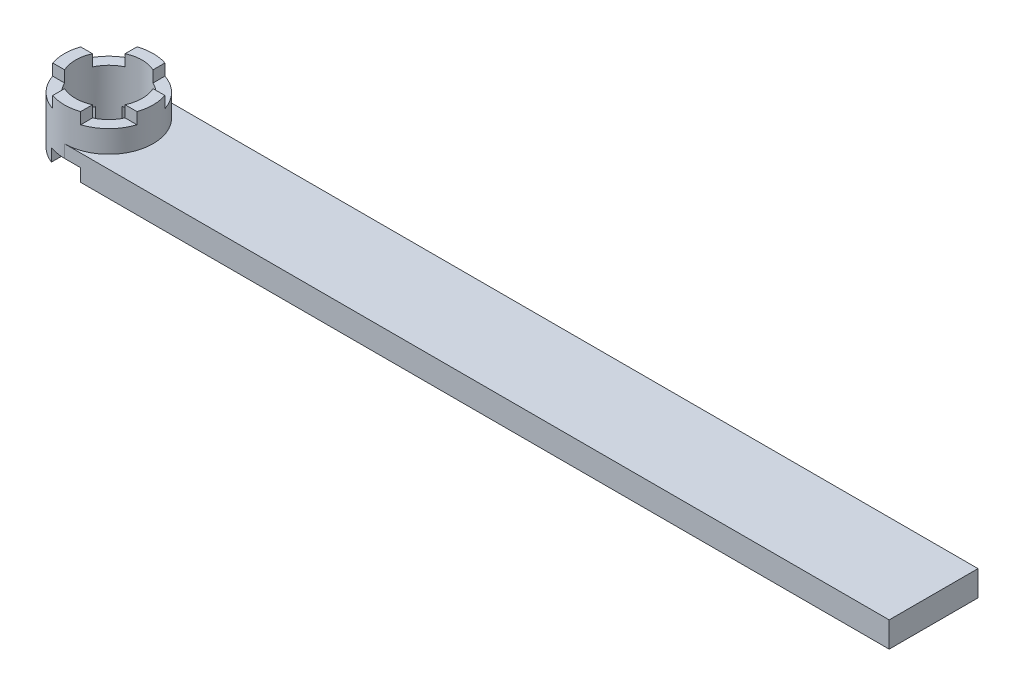
SolidWorks part; units mm, degrees
ref_plane "前视基准面" through (0, 0, 0) normal (0, 0, 1) x (1, 0, 0)
ref_plane "上视基准面" through (0, 0, 0) normal (0, 1, 0) x (1, 0, 0)
ref_plane "右视基准面" through (0, 0, 0) normal (1, 0, 0) x (0, 0, -1)
other "Configuration Table"
sketch "草图1" plane through (0, 0, 0) normal (0, 1, 0) x (1, 0, 0)
  line L1 (0, 7) -> (130, 7)
  line L3 (0, -7) -> (130, -7)
  line L4 (130, 7) -> (130, -7)
  circle A0 centre (0, 0) radius 5.25
  circle A1 centre (0, 0) radius 7
  dimension "D1" = 10.5
  dimension "D2" = 14
  dimension "D3" = 130
extrude "凸台-拉伸3" add sketch "草图1" along normal blind 4 contours A1 L3 L4 L1 | A1 A0
sketch "草图2" plane through (0, 4, 0) normal (0, 1, 0) x (1, 0, 0)
  circle A0 centre (0, 0) radius 7
  arc A1 (0, 7) -> (0, -7) centre (0, 0) ccw construction
  circle A2 centre (0, 0) radius 5.25
  circle A3 centre (0, 0) radius 5.25 construction
extrude "凸台-拉伸4" add sketch "草图2" along normal blind 3.5 contours A0 | A2
sketch "草图3" plane through (0, 0, 0) normal (0, -1, 0) x (1, 0, 0)
  line L0 (0, 0) -> (0, 5.15) construction
  line L1 (0, 0) -> (-6, 0) construction
  line L2 (-2.5, -8.5) -> (2.5, -8.5)
  line L4 (-8, 2.5) -> (-8, -2.5)
  line L5 (-8, -2.5) -> (-2.5, -2.5)
  line L6 (8, 2.5) -> (8, -2.5)
  line L8 (-2.5, 2.5) -> (-2.5, 8.5)
  line L9 (-2.5, 8.5) -> (2.5, 8.5)
  line L10 (2.5, 2.5) -> (2.5, 8.5)
  line L15 (2.5, -2.5) -> (2.5, -8.5)
  line L17 (-2.5, -2.5) -> (-2.5, -8.5)
  line L19 (2.5, -2.5) -> (8, -2.5)
  line L20 (-8, 2.5) -> (-2.5, 2.5)
  line L21 (8, 2.5) -> (2.5, 2.5)
  circle A0 centre (0, 0) radius 7
  arc A1 (0, 7) -> (0, -7) centre (0, 0) ccw construction
  dimension "D1" = 8
  dimension "D2" = 8
  dimension "D4" = 2.5
  dimension "D5" = 2.5
  dimension "D6" = 2.5
  dimension "D7" = 6
extrude "切除-拉伸1" cut sketch "草图3" against normal blind 2 contours L21 L10 L9 L8 L20 L4 L5 L17 L2 L15 L19 L6
sketch "草图4" plane through (0, 7.5, 0) normal (0, 1, 0) x (1, 0, 0)
  line L0 (2.2, 2.2) -> (8.2, 2.2)
  line L5 (8.2, 2.2) -> (8.2, -2.2)
  line L6 (8.2, -2.2) -> (2.2, -2.2)
  line L7 (2.2, -2.2) -> (2.2, -8.2)
  line L8 (2.2, -8.2) -> (-2.2, -8.2)
  line L9 (-2.2, -8.2) -> (-2.2, -2.2)
  line L10 (-2.2, -2.2) -> (-8.2, -2.2)
  line L11 (-8.2, -2.2) -> (-8.2, 2.2)
  line L12 (-8.2, 2.2) -> (-2.2, 2.2)
  line L13 (-2.2, 2.2) -> (-2.2, 8.2)
  line L14 (-2.2, 8.2) -> (2.2, 8.2)
  line L15 (2.2, 8.2) -> (2.2, 2.2)
  line L16 (0, 0) -> (6, 0) construction
  line L18 (0, -6) -> (0, 0) construction
  circle M17 centre (0, 0) radius 7
  circle M18 centre (0, 0) radius 5.25
  dimension "D1" = 2.2
  dimension "D2" = 2.2
  dimension "D3" = 2.2
  dimension "D4" = 2.2
  dimension "D5" = 2.2
  dimension "D6" = 2.2
  dimension "D7" = 2.2
  dimension "D8" = 2.2
  dimension "D9" = 6
  dimension "D10" = 6
  dimension "D11" = 6
  dimension "D12" = 6
extrude "凸台-拉伸5" add sketch "草图4" along normal blind 1.8 contours L12 L10 M17 M18 | L15 L13 M17 M18 | L6 L0 M17 M18 | L9 L7 M17 M18
